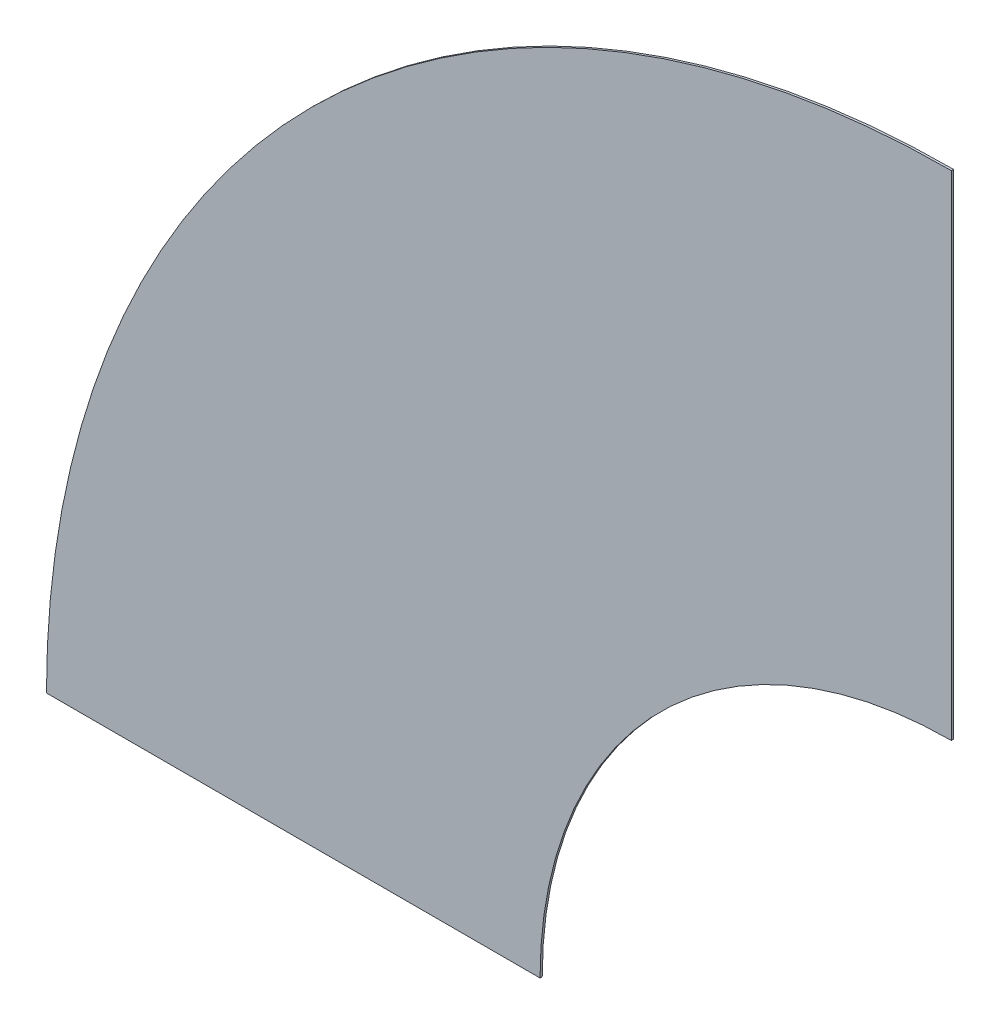
SolidWorks part; units mm, degrees
ref_plane "前视基准面" through (0, 0, 0) normal (0, 0, 1) x (1, 0, 0)
ref_plane "上视基准面" through (0, 0, 0) normal (0, 1, 0) x (1, 0, 0)
ref_plane "右视基准面" through (0, 0, 0) normal (1, 0, 0) x (0, 0, -1)
sketch "草图1" plane through (0, 0, 0) normal (0, 0, 1) x (1, 0, 0)
  arc A0 (0, 600) -> (-600, 0) centre (0, 0) ccw
  dimension "D1" = 600
  dimension "D2" = 90
ref_plane "基准面4" through (0, 600, 0) normal (-1, 0, 0) x (0, 0, 1)
sketch "草图3" plane through (0, 600, 0) normal (-1, 0, 0) x (0, 0, 1)
  line L0 (0, -600) -> (0, 0) construction
  line L1 (-1, 225) -> (1, 225)
  line L2 (-1, 225) -> (-1, -225)
  line L3 (-1, -225) -> (1, -225)
  line L4 (1, 225) -> (1, -225)
  line L5 (-1, 225) -> (1, -225) construction
  line L6 (-1, -225) -> (1, 225) construction
  point P0 (0, 0)
  dimension "D1" = 450
  dimension "D2" = 2
sweep "扫描1" add profiles "草图3" path "草图1"
